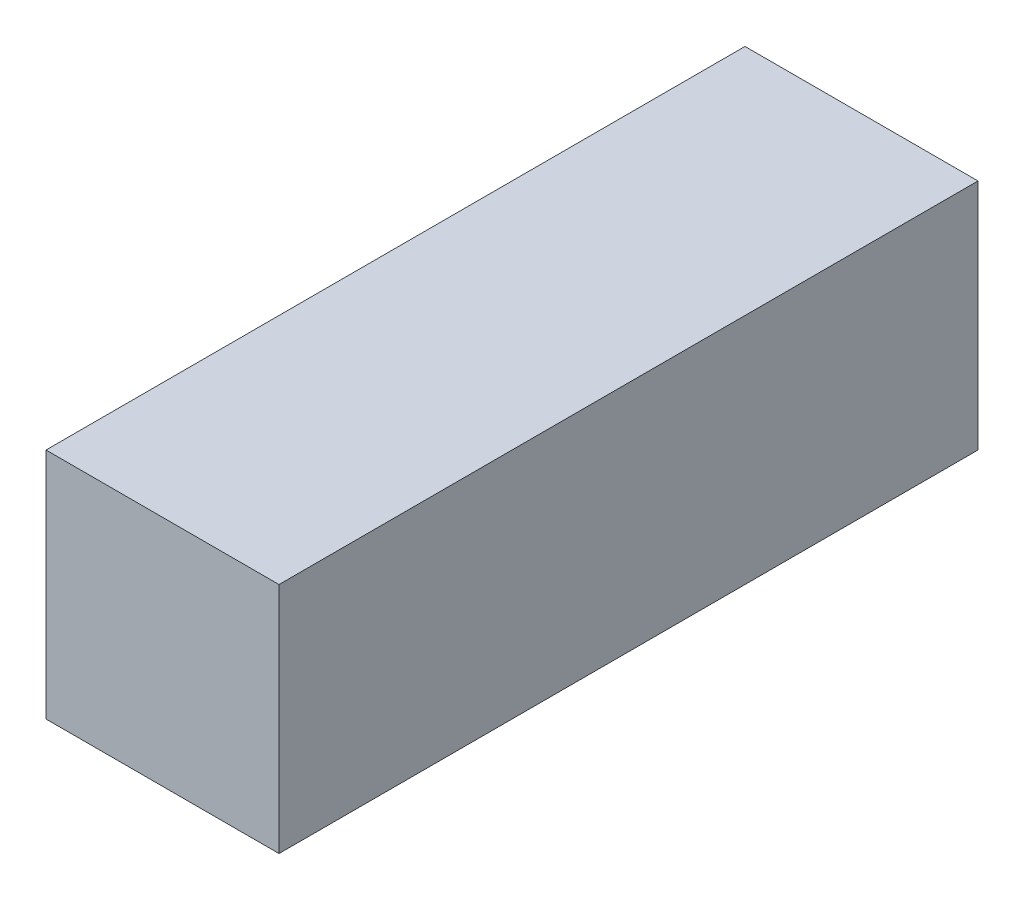
SolidWorks part; units mm, degrees
ref_plane "Front Plane" through (0, 0, 0) normal (0, 0, 1) x (1, 0, 0)
ref_plane "Top Plane" through (0, 0, 0) normal (0, 1, 0) x (1, 0, 0)
ref_plane "Right Plane" through (0, 0, 0) normal (1, 0, 0) x (0, 0, -1)
sketch "Sketch1" plane through (0, 0, 0) normal (0, 0, 1) x (1, 0, 0)
  line L1 (-6.35, -6.35) -> (6.35, -6.35)
  line L2 (-6.35, -6.35) -> (-6.35, 6.35)
  line L3 (-6.35, 6.35) -> (6.35, 6.35)
  line L4 (6.35, -6.35) -> (6.35, 6.35)
  line L5 (-6.35, -6.35) -> (6.35, 6.35) construction
  line L6 (-6.35, 6.35) -> (6.35, -6.35) construction
  point P0 (0, 0)
  dimension "D1" = 12.7
  dimension "D2" = 12.7
extrude "Boss-Extrude1" add sketch "Sketch1" along normal blind 38.1
